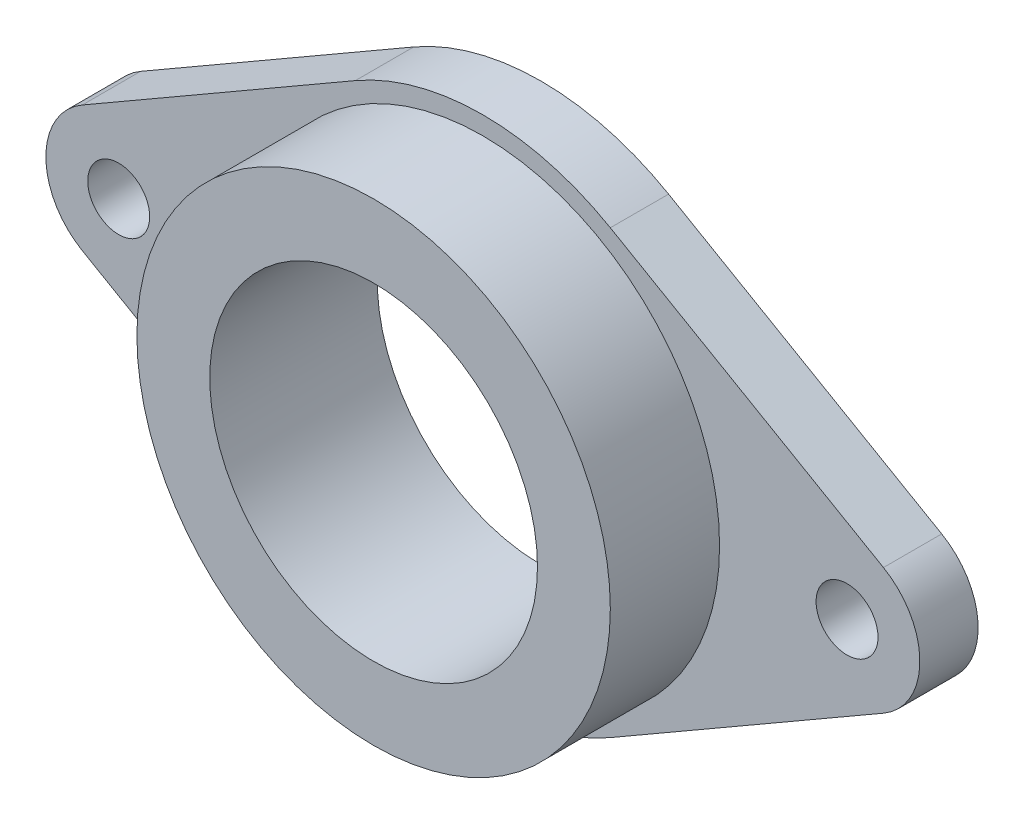
SolidWorks part; units mm, degrees
ref_plane "Front Plane" through (0, 0, 0) normal (0, 0, 1) x (1, 0, 0)
ref_plane "Top Plane" through (0, 0, 0) normal (0, 1, 0) x (1, 0, 0)
ref_plane "Right Plane" through (0, 0, 0) normal (1, 0, 0) x (0, 0, -1)
sketch "Sketch1" plane through (0, 0, 0) normal (0, 0, 1) x (1, 0, 0)
  line L0 (-50, 0) -> (50, 0) construction
  line L1 (-55, 8.6603) -> (-17.5, 30.3109)
  line L2 (0, 25.7502) -> (0, -25.7502) construction
  line L3 (-55, -8.6603) -> (-17.5, -30.3109)
  line L4 (55, -8.6603) -> (17.5, -30.3109)
  line L5 (55, 8.6603) -> (17.5, 30.3109)
  arc A0 (-17.5, -30.3109) -> (17.5, -30.3109) centre (0, 0) ccw
  arc A1 (-55, 8.6603) -> (-55, -8.6603) centre (-50, 0) ccw
  arc A2 (55, -8.6603) -> (55, 8.6603) centre (50, 0) ccw
  arc A3 (17.5, 30.3109) -> (-17.5, 30.3109) centre (0, 0) ccw
  circle A4 centre (-50, 0) radius 4.25
  circle A5 centre (50, 0) radius 4.25
  point P6 (0, 0)
  point P16 (0, 0)
  dimension "D1" = 20
  dimension "D3" = 70
  dimension "D4" = 8.5
  dimension "D2" = 100
extrude "Boss-Extrude1" add sketch "Sketch1" along normal blind 8
sketch "Sketch2" plane through (0, 0, 8) normal (0, 0, 1) x (1, 0, 0)
  line L0 (-50, 0) -> (50, 0) construction
  circle A2 centre (0, 0) radius 32.5
  point P5 (0, 0)
  dimension "D1" = 65
extrude "Boss-Extrude2" add sketch "Sketch2" along normal blind 15
sketch "Sketch3" plane through (0, 0, 23) normal (0, 0, 1) x (1, 0, 0)
  circle A0 centre (0, 0) radius 22.5
  dimension "D1" = 45
extrude "Cut-Extrude1" cut sketch "Sketch3" against normal through all
